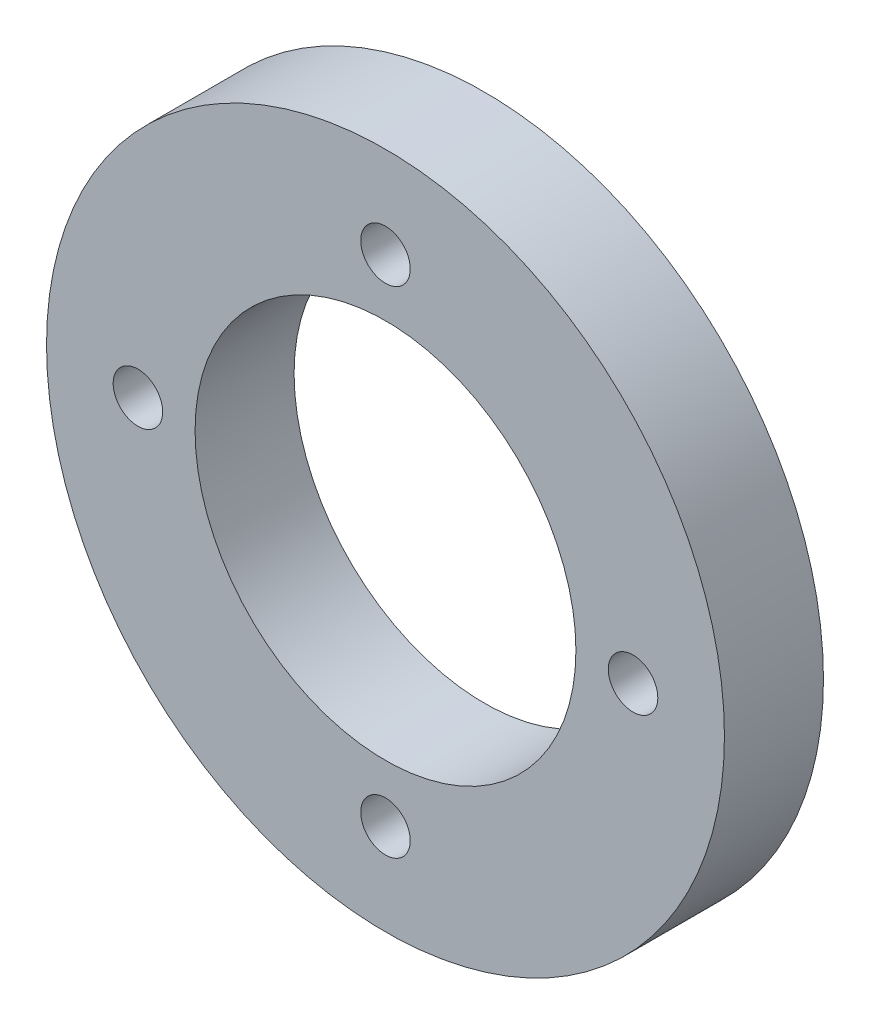
SolidWorks part; units mm, degrees
material "Plain Carbon Steel"
ref_plane "Front Plane" through (0, 0, 0) normal (0, 0, 1) x (1, 0, 0)
ref_plane "Top Plane" through (0, 0, 0) normal (0, 1, 0) x (1, 0, 0)
ref_plane "Right Plane" through (0, 0, 0) normal (1, 0, 0) x (0, 0, -1)
sketch "Sketch1" plane through (0, 0, 0) normal (0, 0, 1) x (1, 0, 0)
  circle A0 centre (0, 0) radius 17.8
  circle A1 centre (0, 0) radius 10
  circle A2 centre (0, 13) radius 1.3
  circle A3 centre (13, 0) radius 1.3
  circle A4 centre (0, -13) radius 1.3
  circle A5 centre (-13, 0) radius 1.3
  point P15 (0, 0)
  dimension "D1" = 35.6
  dimension "D2" = 20
  dimension "D4" = 2.6
  dimension "D3" = 13
  dimension "D5" = 4
extrude "Boss-Extrude1" add sketch "Sketch1" along normal blind 5.2
